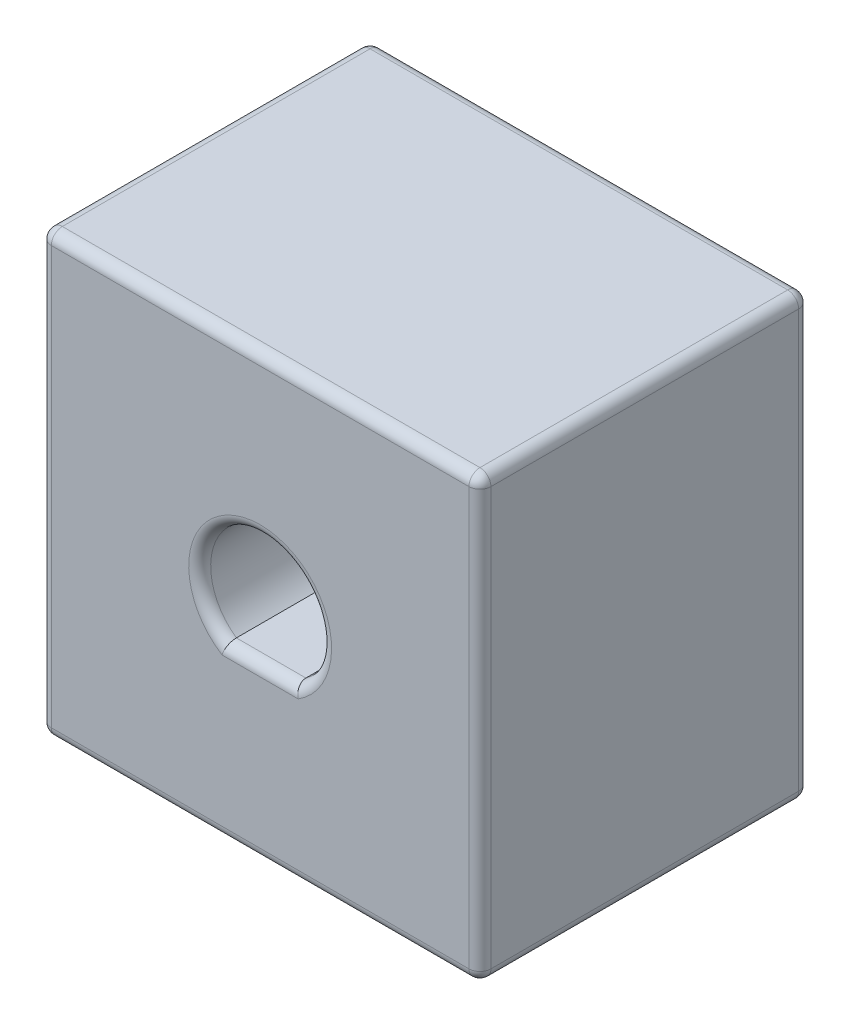
SolidWorks part; units mm, degrees
ref_plane "Plan de face" through (0, 0, 0) normal (0, 0, 1) x (1, 0, 0)
ref_plane "Plan de dessus" through (0, 0, 0) normal (0, 1, 0) x (1, 0, 0)
ref_plane "Plan de droite" through (0, 0, 0) normal (1, 0, 0) x (0, 0, -1)
sketch "Esquisse1" plane through (0, 0, 0) normal (0, 0, 1) x (1, 0, 0)
  line L0 (-1.5811, -2.25) -> (1.5811, -2.25)
  line L1 (-10, -10) -> (10, -10)
  line L2 (-10, -10) -> (-10, 10)
  line L3 (-10, 10) -> (10, 10)
  line L4 (10, -10) -> (10, 10)
  line L5 (-10, -10) -> (10, 10) construction
  line L6 (-10, 10) -> (10, -10) construction
  circle A0 centre (0, 0) radius 2.75
  point P1 (0, 0)
  point P11 (0, -2.25)
  dimension "D2" = 5.5
  dimension "D1" = 2.25
  dimension "D3" = 20
  dimension "D4" = 0.5
extrude "Boss.-Extru.1" add sketch "Esquisse1" along normal blind 15 contours L1 L4 L3 L2 A0 | L0 A0
fillet "Congé1" radius 0.5 16 edges at (10, 10, 7.5) (0, 10, 15) (-10, 10, 7.5) (0, 10, 0) (-10, -10, 7.5) (10, -10, 7.5) (-10, 0, 15) (10, 0, 15) (0, -10, 15) (0, -2.25, 15) (0, 2.75, 15) (10, 0, 0) (-10, 0, 0) (0, -10, 0) (0, -2.25, 0) (0, 2.75, 0)
